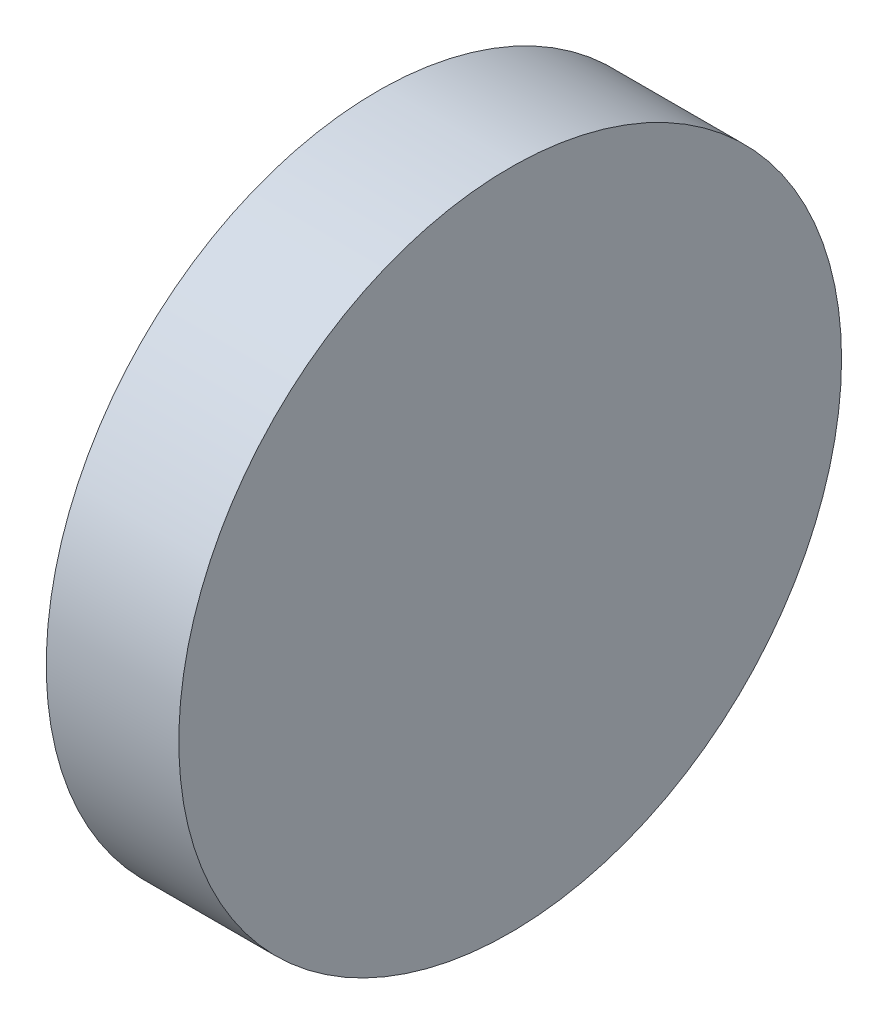
SolidWorks part; units mm, degrees
ref_plane "Front Plane" through (0, 0, 0) normal (0, 0, 1) x (1, 0, 0)
ref_plane "Top Plane" through (0, 0, 0) normal (0, 1, 0) x (1, 0, 0)
ref_plane "Right Plane" through (0, 0, 0) normal (1, 0, 0) x (0, 0, -1)
sketch "Sketch1" plane through (0, 0, 0) normal (1, 0, 0) x (0, 0, -1)
  circle A0 centre (0, 0) radius 12.5
  dimension "D1" = 25
extrude "Boss-Extrude1" add sketch "Sketch1" along normal blind 5 contours A0
